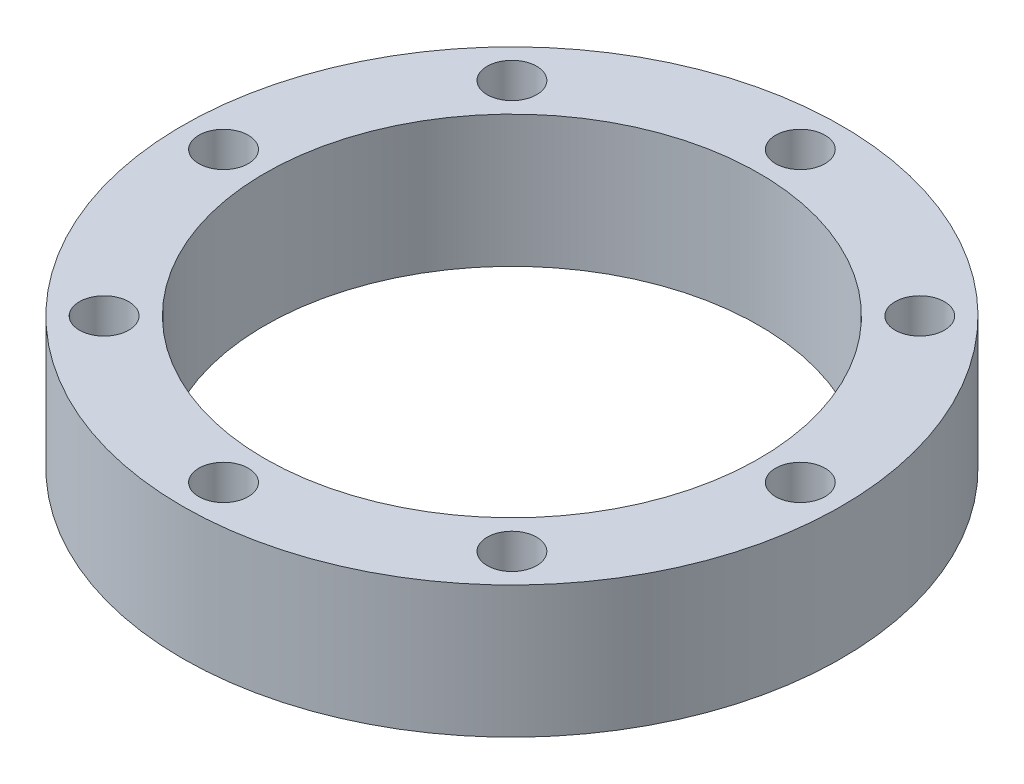
SolidWorks part; units mm, degrees
ref_plane "前视基准面" through (0, 0, 0) normal (0, 0, 1) x (1, 0, 0)
ref_plane "上视基准面" through (0, 0, 0) normal (0, 1, 0) x (1, 0, 0)
ref_plane "右视基准面" through (0, 0, 0) normal (1, 0, 0) x (0, 0, -1)
other "Configuration Table"
sketch "草图1" plane through (0, 0, 0) normal (0, 1, 0) x (1, 0, 0)
  circle A0 centre (0, 0) radius 15
  circle A1 centre (0, 0) radius 20
  circle A3 centre (0, 17.5) radius 1.5
  circle A4 centre (12.3744, 12.3744) radius 1.5
  circle A5 centre (17.5, 0) radius 1.5
  circle A6 centre (12.3744, -12.3744) radius 1.5
  circle A7 centre (0, -17.5) radius 1.5
  circle A8 centre (-12.3744, -12.3744) radius 1.5
  circle A9 centre (-17.5, 0) radius 1.5
  circle A10 centre (-12.3744, 12.3744) radius 1.5
  point P24 (0, 0)
  dimension "D1" = 30
  dimension "D2" = 40
  dimension "D4" = 3
  dimension "D5" = 8
extrude "凸台-拉伸1" add sketch "草图1" along normal blind 8
sketch "草图2" plane through (0, 8, 0) normal (0, 1, 0) x (1, 0, 0)
  line L0 (0, 0) -> (0, 50000) construction
  line L1 (0, 0) -> (35355.3391, 35355.3391) construction
  line L2 (0, 0) -> (19134.1716, 46193.9766) construction
  dimension "D1" = 22.5
